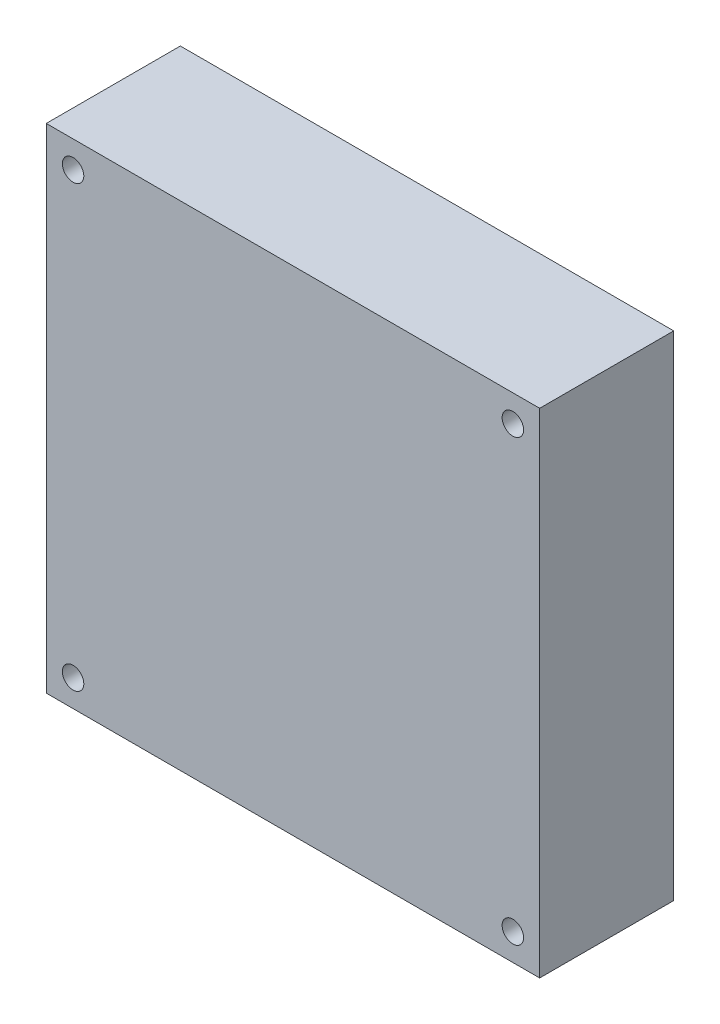
SolidWorks part; units mm, degrees
material "PPE"
ref_plane "Спереди" through (0, 0, 0) normal (0, 0, 1) x (1, 0, 0)
ref_plane "Сверху" through (0, 0, 0) normal (0, 1, 0) x (1, 0, 0)
ref_plane "Справа" through (0, 0, 0) normal (1, 0, 0) x (0, 0, -1)
sketch "Эскиз1" plane through (0, 0, 0) normal (0, 0, 1) x (1, 0, 0)
  line L1 (0, 0) -> (92, 0)
  line L2 (0, 0) -> (0, 92)
  line L3 (0, 92) -> (92, 92)
  line L4 (92, 0) -> (92, 92)
  line L5 (5, 87) -> (87, 87) construction
  line L6 (5, 87) -> (5, 5) construction
  line L7 (5, 5) -> (87, 5) construction
  line L8 (87, 87) -> (87, 5) construction
  circle A0 centre (5, 87) radius 2
  circle A1 centre (87, 87) radius 2
  circle A2 centre (87, 5) radius 2
  circle A3 centre (5, 5) radius 2
  point P9 (46, 87)
  point P10 (46, 92)
  point P11 (5, 46)
  point P12 (0, 46)
  dimension "D3" = 4
  dimension "D1" = 92
  dimension "D2" = 82
extrude "Бобышка-Вытянуть1" add sketch "Эскиз1" along normal blind 25
